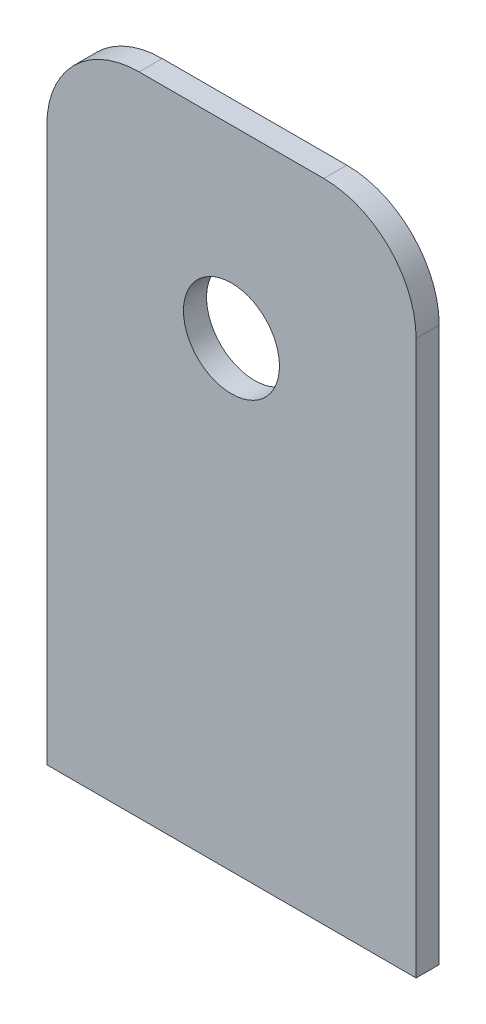
SolidWorks part; units mm, degrees
material "AISI 4130 Steel, annealed at 865C"
ref_plane "Front Plane" through (0, 0, 0) normal (0, 0, 1) x (1, 0, 0)
ref_plane "Top Plane" through (0, 0, 0) normal (0, 1, 0) x (1, 0, 0)
ref_plane "Right Plane" through (0, 0, 0) normal (1, 0, 0) x (0, 0, -1)
sketch "Sketch1" plane through (0, 0, 0) normal (0, 0, 1) x (1, 0, 0)
  line L1 (-12.7, 0) -> (12.7, 0)
  line L2 (-12.7, 0) -> (-12.7, 31.75)
  line L3 (-12.7, 31.75) -> (12.7, 31.75)
  line L4 (12.7, 0) -> (12.7, 31.75)
  line L5 (0, 31.75) -> (0, 0) construction
  line L6 (-12.7, 15.875) -> (12.7, 15.875) construction
  point P248 (0, 15.875)
  dimension "D1" = 25.4
  dimension "D2" = 31.75
extrude "Boss-Extrude1" add sketch "Sketch1" along normal blind 1.5875
sketch "Sketch2" plane through (0, 0, 1.5875) normal (0, 0, 1) x (1, 0, 0)
  line L0 (0, 0) -> (0, 19.05) construction
  line L1 (-12.7, 0) -> (12.7, 0) construction
  circle A0 centre (0, 19.05) radius 3.302
  dimension "D2" = 6.604
  dimension "D1" = 19.05
extrude "Cut-Extrude1" cut sketch "Sketch2" against normal through all both and the other way through all
fillet "Fillet1" radius 6.35 2 edges at (12.7, 31.75, 0.7937) (-12.7, 31.75, 0.7937)
sketch "Sketch3" plane through (0, 0, 0) normal (0, 0, -1) x (-1, 0, 0)
  line L0 (12.7, 25.4) -> (12.7, 0) construction
  line L1 (-12.7, 0) -> (12.7, 0)
  line L2 (-12.7, 0) -> (-12.7, -12.7)
  line L3 (-12.7, -12.7) -> (12.7, -12.7)
  line L4 (12.7, 0) -> (12.7, -12.7)
  line L5 (0, -12.7) -> (0, 0) construction
  line L6 (-12.7, -6.35) -> (12.7, -6.35) construction
  point P112 (0, -6.35)
  dimension "D1" = 12.7
extrude "Boss-Extrude2" add sketch "Sketch3" against normal up to surface (1.5875 mm away) up to face at (-3.302, 19.05, 1.5875)
